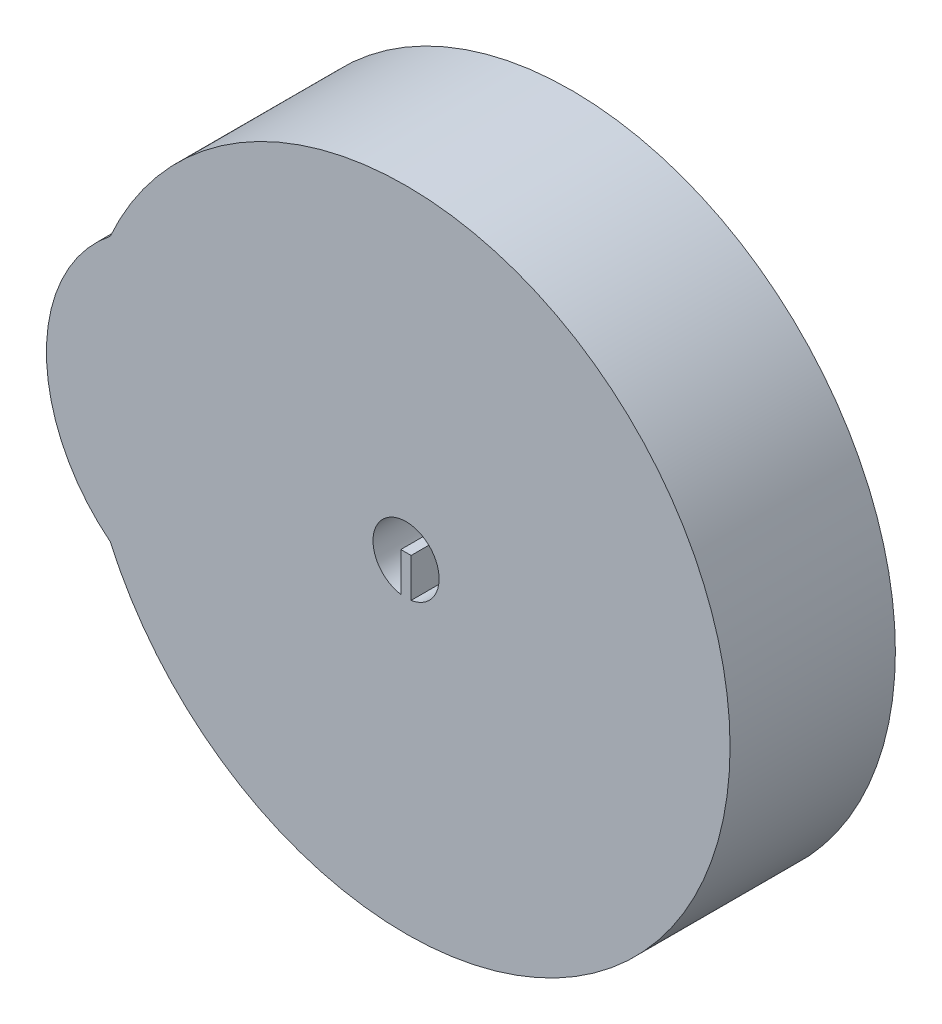
SolidWorks part; units mm, degrees
ref_plane "前视基准面" through (0, 0, 0) normal (0, 0, 1) x (1, 0, 0)
ref_plane "上视基准面" through (0, 0, 0) normal (0, 1, 0) x (1, 0, 0)
ref_plane "右视基准面" through (0, 0, 0) normal (1, 0, 0) x (0, 0, -1)
other "Configuration Table"
sketch "草图1" plane through (0, 0, 0) normal (0, 0, 1) x (1, 0, 0)
  circle A0 centre (0, 0) radius 49
  dimension "D1" = 98
extrude "凸台-拉伸1" add sketch "草图1" along normal blind 25
sketch "草图2" plane through (0, 0, 0) normal (0, 0, -1) x (-1, 0, 0)
  circle A0 centre (0, 0) radius 5
  dimension "D1" = 10
extrude "切除-拉伸1" cut sketch "草图2" against normal blind 25
sketch "草图3" plane through (0, 0, 0) normal (0, 0, -1) x (-1, 0, 0)
  line L0 (0, 0) -> (0, -5.9008) construction
  line L6 (-0.7676, 0.949) -> (0.7882, 0.949)
  line L7 (-0.7676, 0.949) -> (-0.7676, -5.9008)
  line L8 (-0.7676, -5.9008) -> (0.7882, -5.9008)
  line L9 (0.7882, 0.949) -> (0.7882, -5.9008)
extrude "凸台-拉伸4" add sketch "草图3" against normal blind 25
sketch "草图7" plane through (0, 0, 0) normal (0, 0, -1) x (-1, 0, 0)
  line L0 (0, 0) -> (49, 0) construction
  line L1 (44.7325, 20) -> (44.7325, 0) construction
  line L2 (44.7325, 0) -> (44.7325, -20) construction
  circle A0 centre (0, 0) radius 49 construction
  arc A1 (44.7325, 20) -> (44.7325, -20) centre (28.8388, 0) cw
  arc A2 (44.7325, 20) -> (44.7325, -20) centre (0, 0) cw
  dimension "D1" = 20
extrude "凸台-拉伸5" add sketch "草图7" against normal blind 25
